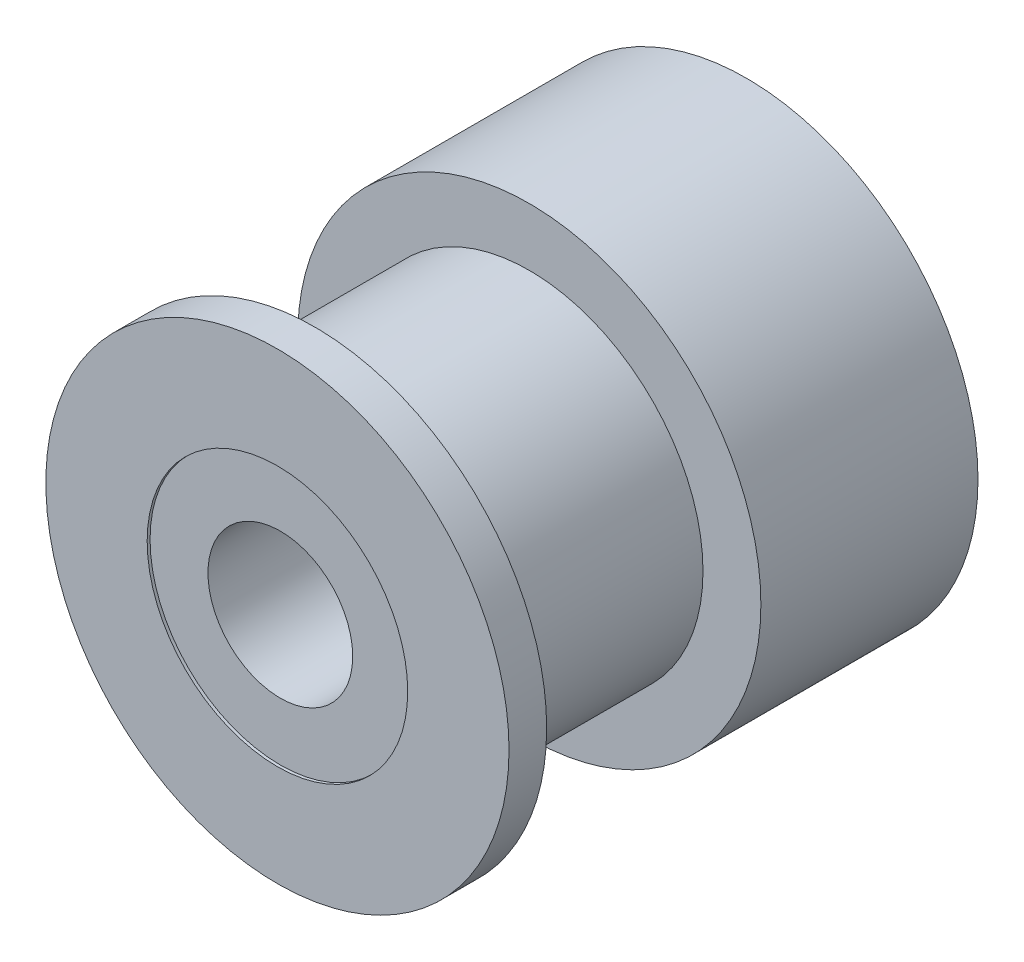
SolidWorks part; units mm, degrees
ref_plane "Front Plane" through (0, 0, 0) normal (0, 0, 1) x (1, 0, 0)
ref_plane "Top Plane" through (0, 0, 0) normal (0, 1, 0) x (1, 0, 0)
ref_plane "Right Plane" through (0, 0, 0) normal (1, 0, 0) x (0, 0, -1)
sketch "Sketch1" plane through (0, 0, 0) normal (0, 0, 1) x (1, 0, 0)
  circle A1 centre (0, 0) radius 8
  dimension "D1" = 16
extrude "Boss-Extrude1" add sketch "Sketch1" along normal blind 7.5
sketch "Sketch2" plane through (0, 0, 7.5) normal (0, 0, 1) x (1, 0, 0)
  circle A0 centre (0, 0) radius 6
  dimension "D1" = 12
extrude "Boss-Extrude2" add sketch "Sketch2" along normal blind 7.4
sketch "Sketch3" plane through (0, 0, 14.9) normal (0, 0, 1) x (1, 0, 0)
  circle A0 centre (0, 0) radius 8
  dimension "D1" = 16
extrude "Boss-Extrude3" add sketch "Sketch3" along normal blind 1.3
sketch "Sketch4" plane through (0, 0, 16.2) normal (0, 0, 1) x (1, 0, 0)
  circle A0 centre (0, 0) radius 2.5
  dimension "D1" = 5
extrude "Cut-Extrude1" cut sketch "Sketch4" against normal blind 20
sketch "Sketch5" plane through (0, 0, 16.2) normal (0, 0, 1) x (1, 0, 0)
  circle A0 centre (0, 0) radius 4.5
extrude "Cut-Extrude2" cut sketch "Sketch5" against normal blind 0.1
sketch "Sketch6" plane through (0, 0, 0) normal (0, 0, -1) x (-1, 0, 0)
  circle A0 centre (0, 0) radius 4.5
extrude "Cut-Extrude3" cut sketch "Sketch6" against normal blind 0.1
sketch "Sketch7" plane through (0, 0, 0) normal (1, 0, 0) x (0, 0, -1)
  line L0 (-7.5, 8) -> (-7.5, -8) construction
  circle A0 centre (-3.75, 0) radius 1.5
  dimension "D2" = 3
  dimension "D1" = 3.75
extrude "Cut-Extrude4" cut sketch "Sketch7" against normal blind 20
sketch "Sketch8" plane through (0, 0, 0) normal (0, 1, 0) x (1, 0, 0)
  line L0 (-6, -7.5) -> (6, -7.5) construction
  circle A0 centre (0, -3.75) radius 1.5
  dimension "D1" = 3.75
extrude "Cut-Extrude5" cut sketch "Sketch8" against normal blind 20
